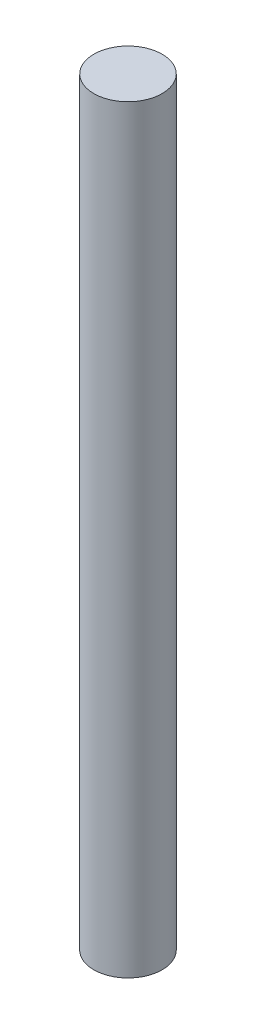
SolidWorks part; units mm, degrees
ref_plane "Front" through (0, 0, 0) normal (0, 0, 1) x (1, 0, 0)
ref_plane "Top" through (0, 0, 0) normal (0, 1, 0) x (1, 0, 0)
ref_plane "Right" through (0, 0, 0) normal (1, 0, 0) x (0, 0, -1)
other "Configuration Table"
sketch "Sketch1" plane through (0, 0, 0) normal (0, 1, 0) x (1, 0, 0)
  circle A0 centre (0, 0) radius 2.25
  dimension "D1" = 4.5
extrude "Extrude1" add sketch "Sketch1" along normal blind 50
